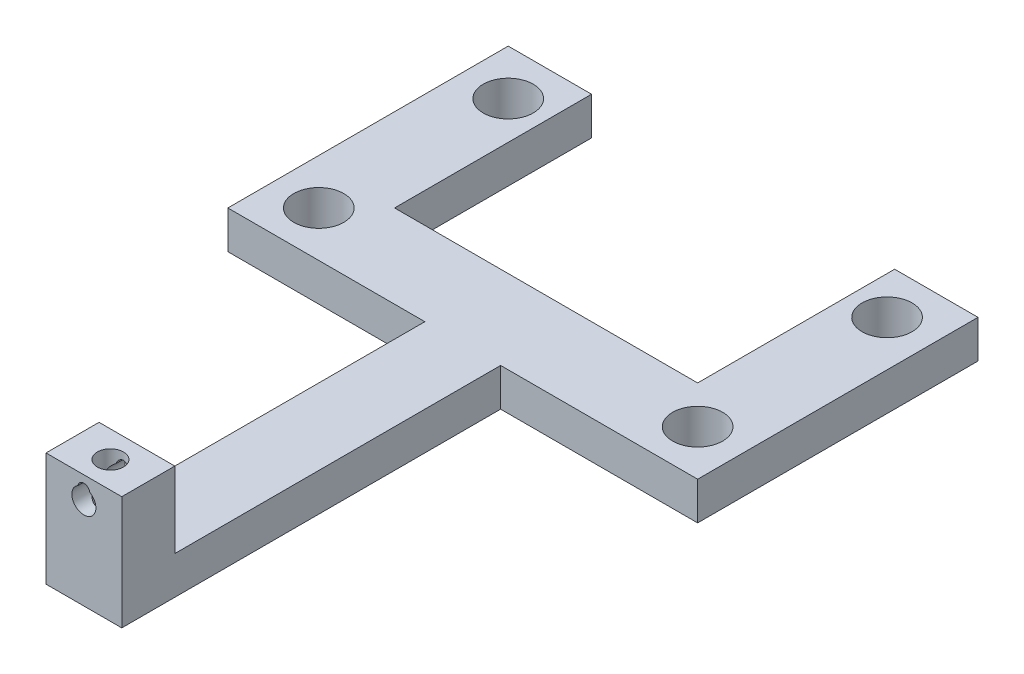
SolidWorks part; units mm, degrees
ref_plane "Front Plane" through (0, 0, 0) normal (0, 0, 1) x (1, 0, 0)
ref_plane "Top Plane" through (0, 0, 0) normal (0, 1, 0) x (1, 0, 0)
ref_plane "Right Plane" through (0, 0, 0) normal (1, 0, 0) x (0, 0, -1)
sketch "Sketch1" plane through (0, 0, 0) normal (0, 1, 0) x (1, 0, 0)
  line L0 (-20, -7.5) -> (-20, 18.5)
  line L1 (-31, -18.5) -> (31, -18.5)
  line L2 (-31, -18.5) -> (-31, 18.5)
  line L3 (-20, -7.5) -> (20, -7.5)
  line L4 (31, -18.5) -> (31, 18.5)
  line L5 (20, -7.5) -> (20, 18.5)
  line L6 (-31, 18.5) -> (-20, 18.5)
  line L7 (20, 18.5) -> (31, 18.5)
  point P0 (0, 0)
  dimension "D1" = 62
  dimension "D2" = 37
  dimension "D3" = 11
extrude "Extrude1" add sketch "Sketch1" along normal blind 5
sketch "Sketch3" plane through (0, 5, 0) normal (0, 1, 0) x (-1, 0, 0)
  line L0 (0, -31.5247) -> (0, 28.6528) construction
  line L1 (37.379, 0) -> (-40.4533, 0) construction
hole_wizard "M6 Clearance Hole1" positions "3DSketch2" profile "Sketch4" hole size "M6" standard "Ansi Metric"
sketch3d "3DSketch2"
  line L0 (-37.379, 5, 0) -> (40.4533, 5, 0) construction
  line L1 (0, 5, -31.5247) -> (0, 5, 28.6528) construction
  point P0 (-25, 5, -12.5)
  dimension "D1" = 12.5
  dimension "D2" = 25
sketch "Sketch4" plane through (-25, 5, -12.5) normal (1, 0, 0) x (0, 0, 1)
  line L0 (0, 0) -> (0, 11.9828)
  line L1 (0, 11.9828) -> (3.3, 10)
  line L2 (3.3, 10) -> (3.3, 0)
  line L5 (3.3, 0) -> (0, 0)
  line L10 (0, 11.9828) -> (-3.3, 10) construction
  line L11 (0, -6.35) -> (0, 107.95) construction
  dimension "Hole Dia." = 6.6
  dimension "Hole Depth" = 10
  dimension "Drill Angle" = 118
pattern_linear "LPattern1" count 2 spacing 50 along (1, 0, 0) count 2 spacing 25 along (0, 0, 1) of "M6 Clearance Hole1"
sketch "Sketch5" plane through (0, 0, 18.5) normal (0, 0, 1) x (1, 0, 0)
  line L0 (-31, 0) -> (31, 0) construction
  line L1 (-5, 0) -> (5, 0)
  line L2 (-5, 0) -> (-5, 5)
  line L3 (-5, 5) -> (5, 5)
  line L4 (5, 0) -> (5, 5)
  line L5 (-31, 5) -> (31, 5) construction
  dimension "D1" = 5
  dimension "D2" = 5
extrude "Extrude2" add sketch "Sketch5" along normal blind 50
sketch "Sketch6" plane through (0, 5, 0) normal (0, 1, 0) x (1, 0, 0)
  line L0 (5, -68.5) -> (5, -18.5) construction
  line L1 (-5, -68.5) -> (5, -68.5)
  line L2 (-5, -68.5) -> (-5, -61.5)
  line L3 (-5, -61.5) -> (5, -61.5)
  line L4 (5, -68.5) -> (5, -61.5)
  dimension "D1" = 7
extrude "Extrude3" add sketch "Sketch6" along normal blind 10
hole_wizard "1/8 (0.125) Diameter Hole1" positions "3DSketch3" profile "Sketch8" hole size "1/8" standard "Ansi Inch" end condition through all
sketch3d "3DSketch3"
  line L0 (5, 15, 61.5) -> (5, 5, 61.5) construction
  line L1 (5, 15, 61.5) -> (-5, 15, 61.5) construction
  point P0 (0, 12, 61.5)
  dimension "D1" = 5
  dimension "D2" = 3
sketch "Sketch8" plane through (0, 12, 61.5) normal (1, 0, 0) x (0, 1, 0)
  line L0 (0, 0) -> (0, 7)
  line L1 (0, 7) -> (1.5875, 7)
  line L2 (1.5875, 7) -> (1.5875, 0)
  line L5 (1.5875, 0) -> (0, 0)
  line L11 (0, -6.35) -> (0, 107.95) construction
  dimension "Thru Hole Dia." = 3.175
  dimension "Thru Hole Depth" = 7
hole_wizard "1/16 (0.0625) Diameter Hole1" positions "3DSketch5" profile "Sketch11" hole size "1/16" standard "Ansi Inch" end condition through all
sketch3d "3DSketch5"
  line L0 (5, 15, 61.5) -> (5, 5, 61.5) construction
  line L1 (5, 15, 61.5) -> (-5, 15, 61.5) construction
  point P0 (0, 13.25, 61.5)
  dimension "D1" = 5
  dimension "D2" = 1.75
sketch "Sketch11" plane through (0, 13.25, 61.5) normal (1, 0, 0) x (0, 1, 0)
  line L0 (0, 0) -> (0, 7)
  line L1 (0, 7) -> (0.7937, 7)
  line L2 (0.7937, 7) -> (0.7937, 0)
  line L5 (0.7937, 0) -> (0, 0)
  line L11 (0, -6.35) -> (0, 107.95) construction
  dimension "Thru Hole Dia." = 1.5875
  dimension "Thru Hole Depth" = 7
hole_wizard "#8-32 Tapped Hole1" positions "3DSketch6" profile "Sketch13" tap size "#8-32" standard "Ansi Inch" end condition through all
sketch3d "3DSketch6"
  line L0 (-5, 0, 68.5) -> (-5, 0, 18.5) construction
  line L1 (-5, 0, 68.5) -> (5, 0, 68.5) construction
  point P0 (0, 0, 65)
  dimension "D1" = 5
  dimension "D2" = 3.5
sketch "Sketch13" plane through (0, 0, 65) normal (1, 0, 0) x (0, 0, -1)
  line L0 (0, 0) -> (0, 15)
  line L1 (0, 15) -> (1.7272, 15)
  line L2 (1.7272, 15) -> (1.7272, 0)
  line L5 (1.7272, 0) -> (0, 0)
  line L11 (0, -6.35) -> (0, 107.95) construction
  dimension "Thread Major Dia." = 3.4544
  dimension "Thru Tap Drill Depth" = 15
